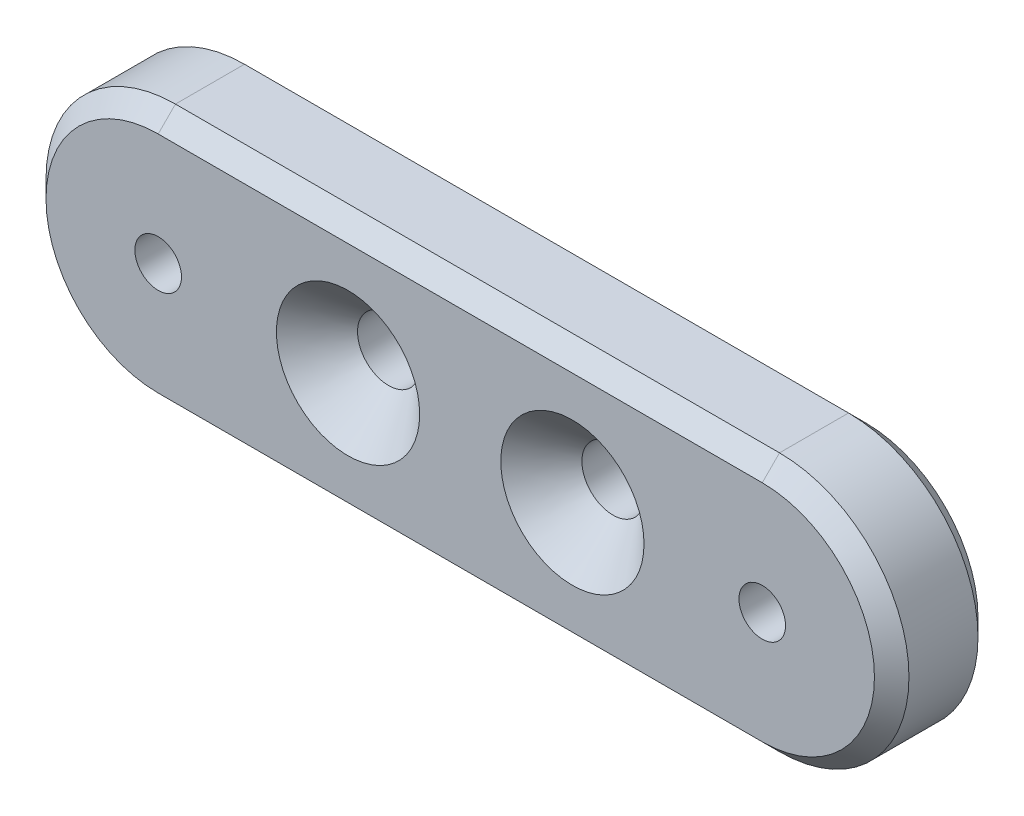
SolidWorks part; units mm, degrees
material "ABS"
ref_plane "Front Plane" through (0, 0, 0) normal (0, 0, 1) x (1, 0, 0)
ref_plane "Top Plane" through (0, 0, 0) normal (0, 1, 0) x (1, 0, 0)
ref_plane "Right Plane" through (0, 0, 0) normal (1, 0, 0) x (0, 0, -1)
sketch "Sketch1" plane through (0, 0, 0) normal (0, 0, 1) x (1, 0, 0)
  line L0 (-17.5, 0) -> (17.5, 0) construction
  line L1 (-17.5, 7.5) -> (17.5, 7.5)
  line L2 (-17.5, -7.5) -> (17.5, -7.5)
  arc A0 (-17.5, 7.5) -> (-17.5, -7.5) centre (-17.5, 0) ccw
  arc A1 (17.5, -7.5) -> (17.5, 7.5) centre (17.5, 0) ccw
  circle A2 centre (-17.5, 0) radius 1.35
  circle A3 centre (17.5, 0) radius 1.35
  point P2 (0, 0)
  dimension "D3" = 2.7
  dimension "D1" = 35
  dimension "D2" = 15
extrude "Boss-Extrude1" add sketch "Sketch1" along normal blind 6
chamfer "Chamfer1" distance 1 angle 45 8 edges at (0, -7.5, 0) (25, 0, 0) (-25, 0, 0) (0, 7.5, 0) (0, -7.5, 6) (25, 0, 6) (-25, 0, 6) (0, 7.5, 6)
hole_wizard "CSK for M3 Countersunk Flat Head Screw1" positions "Sketch2" profile "Sketch3" countersink size "M3" standard "ISO" end condition up to next
sketch "Sketch2" plane through (0, 0, 6) normal (0, 0, 1) x (1, 0, 0)
  arc A0 (-17.5, 6.5) -> (-17.5, -6.5) centre (-17.5, 0) ccw construction
  circle A1 centre (-17.5, 0) radius 1.35 construction
  circle A2 centre (17.5, 0) radius 1.35 construction
  point P6 (6.5, 0)
  point P8 (-6.5, 0)
  point P17 (-24, 0)
  dimension "D1" = 11
  dimension "D2" = 11
sketch "Sketch3" plane through (6.5, 0, 6) normal (1, 0, 0) x (0, -1, 0)
  line L0 (0, 0) -> (0, 6)
  line L1 (0, 6) -> (1.825, 6)
  line L2 (1.8, 5.975) -> (1.8, 2.35)
  line L3 (1.8, 2.35) -> (4.15, 0)
  line L5 (4.15, 0) -> (0, 0)
  line L6 (-1.8, 2.35) -> (-4.15, 0) construction
  line L7 (1.825, 6) -> (1.8, 5.975)
  line L8 (-1.825, 6) -> (-1.8, 5.975) construction
  line L11 (0, -6.35) -> (0, 107.95) construction
  dimension "Thru Hole Dia." = 3.6
  dimension "Thru Hole Depth" = 6
  dimension "Near C'Sink Dia." = 8.3
  dimension "Near C'Sink Angle" = 90
  dimension "Far C'Sink Dia." = 3.65
  dimension "Far C'Sink Angle" = 90
